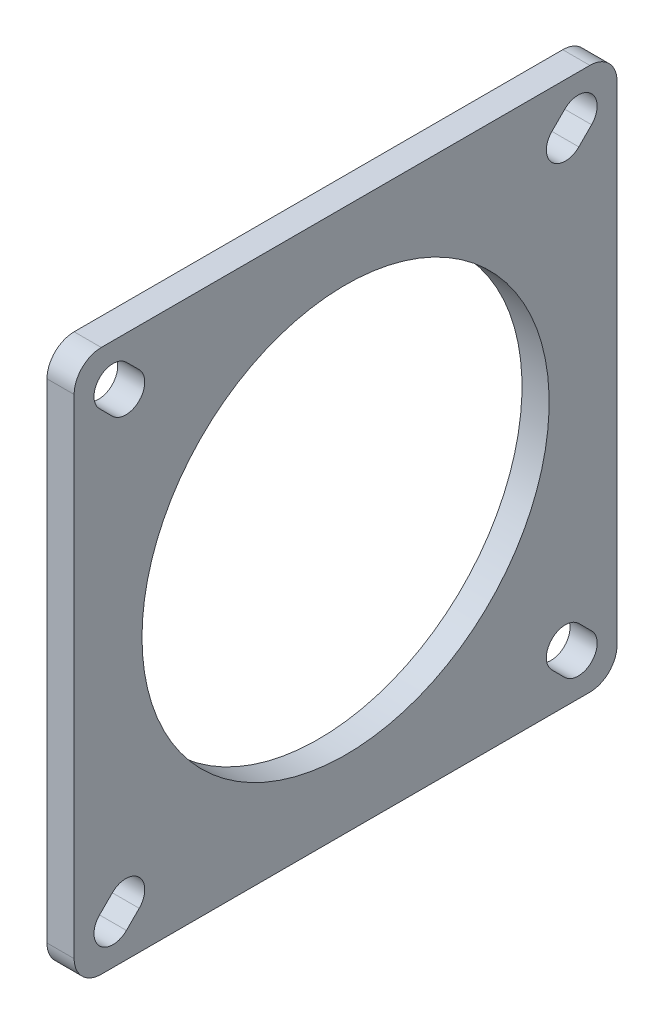
SolidWorks part; units mm, degrees
material "1060 Сплав"
ref_plane "Спереди" through (0, 0, 0) normal (0, 0, 1) x (1, 0, 0)
ref_plane "Сверху" through (0, 0, 0) normal (0, 1, 0) x (1, 0, 0)
ref_plane "Справа" through (0, 0, 0) normal (1, 0, 0) x (0, 0, -1)
sketch "Эскиз1" plane through (0, 0, 0) normal (0, 0, 1) x (1, 0, 0)
  line L0 (0, 22.5) -> (0, 50)
  line L1 (0, 50) -> (3, 50)
  line L2 (3, 50) -> (3, 22.5)
  line L3 (3, 22.5) -> (0, 22.5)
  line L4 (-29.3651, 0) -> (90.6978, 0) construction
  dimension "D1" = 45
  dimension "D2" = 100
  dimension "D3" = 3
revolve "Повернуть1" add sketch "Эскиз1" angle 360 about L4
sketch "Эскиз7" plane through (0, 0, 0) normal (-1, 0, 0) x (0, 0, 1)
  line L1 (30, -30) -> (-30, -30)
  line L2 (30, -30) -> (30, 30)
  line L3 (30, 30) -> (-30, 30)
  line L4 (-30, -30) -> (-30, 30)
  circle A0 centre (0, 0) radius 50 construction
  circle A1 centre (0, 0) radius 50
  point P0 (0, 0)
  dimension "D1" = 60
  dimension "D2" = 60
  dimension "D3" = 30
  dimension "D4" = 30
extrude "Вырез-Вытянуть4" cut sketch "Эскиз7" against normal through all both and the other way through all
sketch "Эскиз6" plane through (0, 0, 0) normal (-1, 0, 0) x (0, 0, 1)
  line L0 (-27.192, 24.2222) -> (-25.7778, 22.808)
  line L1 (-24.2222, 27.192) -> (-22.808, 25.7778)
  line L2 (0, 0) -> (0, 50000) construction
  line L4 (-26.4849, 23.5151) -> (-23.5151, 26.4849) construction
  line L5 (-15.9099, 15.9099) -> (35339.4292, -35339.4292) construction
  arc A0 (-24.2222, 27.192) -> (-27.192, 24.2222) centre (-25.7071, 25.7071) ccw
  arc A1 (-25.7778, 22.808) -> (-22.808, 25.7778) centre (-24.2929, 24.2929) ccw
  circle A2 centre (0, 0) radius 35.3553 construction
  point P11 (-25, 25)
  dimension "D1" = 2
  dimension "D3" = 25
  dimension "D2" = 4.2
  dimension "D4" = 45
extrude "Вырез-Вытянуть3" cut sketch "Эскиз6" against normal through all both and the other way through all
pattern_circular "Круговой массив2" count 4 over 360 about axis through (0, 0, 0) along (1, 0, 0) of "Вырез-Вытянуть3"
fillet "Скругление1" radius 3 4 edges at (1.5, -30, -30) (1.5, -30, 30) (1.5, 30, 30) (1.5, 30, -30)
